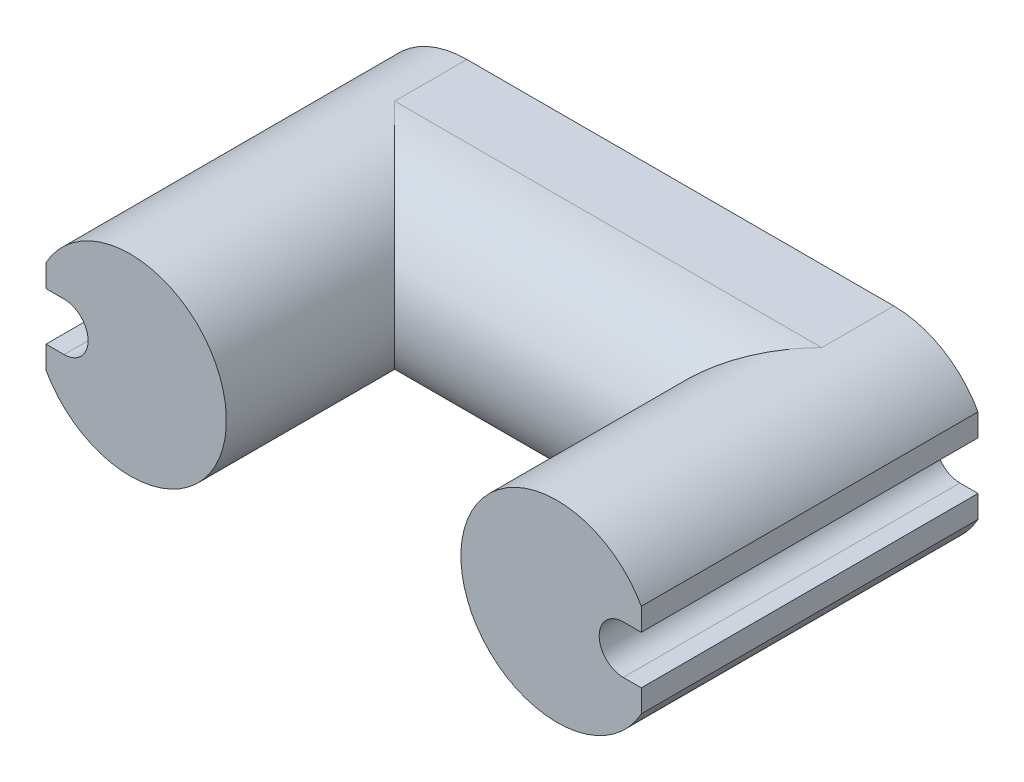
SolidWorks part; units mm, degrees
ref_plane "Спереди" through (0, 0, 0) normal (0, 0, 1) x (1, 0, 0)
ref_plane "Сверху" through (0, 0, 0) normal (0, 1, 0) x (1, 0, 0)
ref_plane "Справа" through (0, 0, 0) normal (1, 0, 0) x (0, 0, -1)
sketch "Эскиз1" plane through (0, 0, 0) normal (0, 0, 1) x (1, 0, 0)
  line L0 (-17.75, 0) -> (46.9247, 0) construction
  line L1 (-23.25, 2) -> (-24.75, 2)
  line L2 (-23.25, -2) -> (-24.75, -2)
  line L3 (0, 0) -> (0, -21.8693) construction
  line L4 (23.25, -2) -> (24.75, -2)
  line L5 (23.25, 2) -> (24.75, 2)
  line L6 (-24.75, -3.873) -> (-24.75, -2)
  line L7 (-24.75, 2) -> (-24.75, 3.873)
  line L8 (24.75, -3.873) -> (24.75, -2)
  line L9 (24.75, 2) -> (24.75, 3.873)
  arc A0 (-24.75, -3.873) -> (-24.75, 3.873) centre (-17.75, 0) ccw
  arc A1 (-23.25, -2) -> (-23.25, 2) centre (-23.25, 0) ccw
  arc A2 (23.25, -2) -> (23.25, 2) centre (23.25, 0) cw
  arc A3 (24.75, -3.873) -> (24.75, 3.873) centre (17.75, 0) cw
  dimension "D1" = 16
  dimension "D2" = 17.75
  dimension "D3" = 4
  dimension "D4" = 5.5
  dimension "D5" = 24.75
extrude "Вытянуть1" add sketch "Эскиз1" against normal blind 28
sketch "Эскиз2" plane through (0, 0, 0) normal (1, 0, 0) x (0, 0, -1)
  line L0 (0, 0) -> (32.048, 0) construction
  line L2 (0, 2) -> (0, 3.873) construction
  line L3 (28, -8) -> (28, 8) construction
  line L4 (28, -8) -> (28, 8)
  line L5 (28, 8) -> (22, 8)
  line L6 (28, -8) -> (22, -8)
  arc A0 (22, 8) -> (22, -8) centre (22, 0) ccw
  dimension "D1" = 16
  dimension "D2" = 14
extrude "Вытянуть2" add sketch "Эскиз2" against normal up to surface and the other way up to surface
